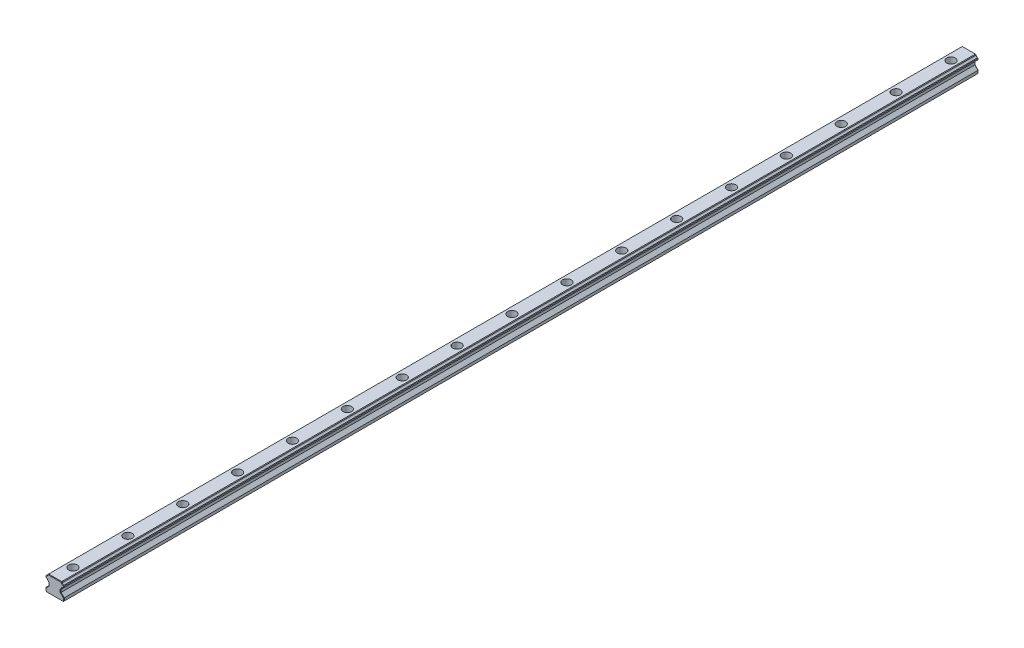
SolidWorks part; units mm, degrees
ref_plane "Front Plane" through (0, 0, 0) normal (0, 0, 1) x (1, 0, 0)
ref_plane "Top Plane" through (0, 0, 0) normal (0, 1, 0) x (1, 0, 0)
ref_plane "Right Plane" through (0, 0, 0) normal (1, 0, 0) x (0, 0, -1)
sketch "Sketch1" plane through (-20, 0, 0) normal (0, 0, 1) x (1, 0, 0)
  line L0 (10, -4.9999) -> (10, -8)
  line L1 (10, -8) -> (11, -9)
  line L2 (11, -9) -> (20, -9)
  line L3 (17, 9) -> (23, 9)
  line L5 (26.55, -1.55) -> (30, -4.9999)
  line L6 (26.55, 1.3792) -> (26.55, -1.55)
  line L7 (27.7679, 2.5951) -> (26.55, 1.3792)
  line L8 (30, 4.8292) -> (29.4727, 4.3144)
  line L9 (30, 6.16) -> (30, 4.8292)
  line L10 (29.4727, 6.6874) -> (30, 6.16)
  line L11 (27.16, 9) -> (27.7679, 8.3921)
  line L13 (29, -9) -> (20, -9)
  line L14 (30, -8) -> (29, -9)
  line L15 (30, -4.9999) -> (30, -8)
  line L16 (27.16, 9) -> (12.84, 9)
  line L17 (12.84, 9) -> (12.2321, 8.3921)
  line L18 (10.5273, 6.6874) -> (10, 6.16)
  line L19 (10, 6.16) -> (10, 4.8292)
  line L20 (10, 4.8292) -> (10.5273, 4.3144)
  line L21 (12.2321, 2.5951) -> (13.45, 1.3792)
  line L22 (13.45, 1.3792) -> (13.45, -1.55)
  line L23 (13.45, -1.55) -> (10, -4.9999)
  line L25 (20, -9) -> (20, 9) construction
  arc A0 (29.4727, 4.3144) -> (27.7679, 2.5951) centre (29.8039, 2.2812) ccw
  arc A1 (27.7679, 8.3921) -> (29.4727, 6.6874) centre (29.8015, 8.7209) ccw
  arc A2 (12.2321, 8.3921) -> (10.5273, 6.6874) centre (10.1985, 8.7209) cw
  arc A3 (10.5273, 4.3144) -> (12.2321, 2.5951) centre (10.1961, 2.2812) cw
  point P3 (20, 0.5)
  point P37 (20, 0)
  point P42 (20, 9)
  dimension "D17" = 2.06
  dimension "Rail Width" = 20
  dimension "D2" = 1
  dimension "D3" = 1
  dimension "D4" = 6
  dimension "D7" = 18
  dimension "D8" = 4.0001
  dimension "D9" = 10.55
  dimension "D10" = 13.1001
  dimension "D11" = 15.5359
  dimension "D12" = 0.6079
  dimension "D13" = 0.6079
  dimension "D15" = 0.5273
  dimension "D16" = 0.5273
  dimension "D18" = 1.2159
  dimension "D19" = 0.5148
  dimension "D20" = 6.4049
  dimension "D21" = 2.84
  dimension "D22" = 4.1708
  dimension "Rail Height" = 18
  dimension "Mounting Hole Dpeth" = 8.5
sketch "Sketch2" plane through (0, 0, 0) normal (1, 0, 0) x (0, 0, -1)
  line L0 (-480, 9) -> (-475.25, 9)
  line L1 (-475.25, 9) -> (-475.25, 0.5)
  line L2 (-475.25, 0.5) -> (-477, 0.5)
  line L3 (-477, 0.5) -> (-477, -9)
  line L4 (-477, -9) -> (-480, -9)
  line L5 (-480, -9) -> (-480, 9) construction
  line L6 (-480, -9) -> (-480, 9) construction
  line L7 (410, 0) -> (-410, 0)
  line L9 (-480, 9) -> (-480, -9)
  line L10 (500, 0) -> (-500, 0) construction
  point P6 (-360, 0)
  point P7 (-480, 0)
  point P8 (-300, 0)
  point P11 (0, 0)
  point P12 (-420, 0)
  point P13 (-180, 0)
  point P14 (-410, 0)
  point P18 (-120, 0)
  point P21 (0, 0)
  point P22 (410, 0)
  point P24 (-240, 0)
  point P25 (-60, 0)
  point P26 (0, 0)
  point P27 (60, 0)
  point P28 (120, 0)
  point P29 (180, 0)
  point P30 (240, 0)
  point P31 (300, 0)
  point P32 (360, 0)
  point P33 (420, 0)
  point P34 (480, 0)
  point P35 (410, -1)
  dimension "D1" = 9.5
  dimension "D3" = 6
  dimension "Rail Length" = 1000
  dimension "Mounting Hole Center-to-End" = 20
  dimension "Mounting Hole Center-to-Center" = 60
  dimension "D2" = 90
  dimension "D4" = 1
  dimension "Number of Mounting Holes" = 17
sketch "Sketch3" plane through (0, 0, 0) normal (0, 0, 1) x (1, 0, 0)
  line L0 (-3, 9) -> (3, 9) construction
  line L3 (-3, 9) -> (3, 9)
  line L21 (0, -9) -> (9, -9)
  line L22 (9, -9) -> (10, -8)
  line L23 (10, -8) -> (10, -4.9999)
  line L24 (10, -4.9999) -> (6.55, -1.55)
  line L25 (6.55, -1.55) -> (6.55, 1.3792)
  line L26 (6.55, 1.3792) -> (7.7679, 2.5951)
  line L27 (9.4727, 4.3144) -> (10, 4.8292)
  line L28 (10, 4.8292) -> (10, 6.16)
  line L29 (10, 6.16) -> (9.4727, 6.6874)
  line L30 (7.7679, 8.3921) -> (7.16, 9)
  line L31 (7.16, 9) -> (-7.16, 9)
  line L32 (-7.16, 9) -> (-7.7679, 8.3921)
  line L33 (-9.4727, 6.6874) -> (-10, 6.16)
  line L34 (-10, 6.16) -> (-10, 4.8292)
  line L35 (-10, 4.8292) -> (-9.4727, 4.3144)
  line L36 (-7.7679, 2.5951) -> (-6.55, 1.3792)
  line L37 (-6.55, 1.3792) -> (-6.55, -1.55)
  line L38 (-6.55, -1.55) -> (-10, -4.9999)
  line L39 (-10, -4.9999) -> (-10, -8)
  line L40 (-10, -8) -> (-9, -9)
  line L41 (-9, -9) -> (0, -9)
  line L42 (0, -9) -> (9, -9)
  line L43 (9, -9) -> (10, -8)
  line L44 (10, -8) -> (10, -4.9999)
  line L45 (10, -4.9999) -> (6.55, -1.55)
  line L46 (6.55, -1.55) -> (6.55, 1.3792)
  line L47 (6.55, 1.3792) -> (7.7679, 2.5951)
  line L48 (9.4727, 4.3144) -> (10, 4.8292)
  line L49 (10, 4.8292) -> (10, 6.16)
  line L50 (10, 6.16) -> (9.4727, 6.6874)
  line L51 (7.7679, 8.3921) -> (7.16, 9)
  line L52 (7.16, 9) -> (-7.16, 9)
  line L53 (-7.16, 9) -> (-7.7679, 8.3921)
  line L54 (-9.4727, 6.6874) -> (-10, 6.16)
  line L55 (-10, 6.16) -> (-10, 4.8292)
  line L56 (-10, 4.8292) -> (-9.4727, 4.3144)
  line L57 (-7.7679, 2.5951) -> (-6.55, 1.3792)
  line L58 (-6.55, 1.3792) -> (-6.55, -1.55)
  line L59 (-6.55, -1.55) -> (-10, -4.9999)
  line L60 (-10, -4.9999) -> (-10, -8)
  line L61 (-10, -8) -> (-9, -9)
  line L62 (-9, -9) -> (0, -9)
  arc A4 (9.4727, 4.3144) -> (7.7679, 2.5951) centre (9.8039, 2.2812) ccw
  arc A5 (7.7679, 8.3921) -> (9.4727, 6.6874) centre (9.8015, 8.7209) ccw
  arc A6 (-9.4727, 6.6874) -> (-7.7679, 8.3921) centre (-9.8015, 8.7209) ccw
  arc A7 (-7.7679, 2.5951) -> (-9.4727, 4.3144) centre (-9.8039, 2.2812) ccw
  arc A8 (9.4727, 4.3144) -> (7.7679, 2.5951) centre (9.8039, 2.2812) ccw
  arc A9 (7.7679, 8.3921) -> (9.4727, 6.6874) centre (9.8015, 8.7209) ccw
  arc A10 (-9.4727, 6.6874) -> (-7.7679, 8.3921) centre (-9.8015, 8.7209) ccw
  arc A11 (-7.7679, 2.5951) -> (-9.4727, 4.3144) centre (-9.8039, 2.2812) ccw
  dimension "D1" = 0
extrude "Boss-Extrude1" add sketch "Sketch3" along normal up to vertex (500 mm away) and the other way up to vertex (500 mm away) contours A11 L57 L58 L59 L60 L61 L62 L42 L43 L44 L45 L46 L47 A8 L48 L49 L50 A9 L51 L52 L3 L53 A10 L54 L55 L56 up to point (0, 0, 500) other way up to point (0, 0, -500)
sketch "Sketch4" plane through (0, 0, 0) normal (1, 0, 0) x (0, 0, -1)
  line L6 (-475.25, 9) -> (-480, 9)
  line L7 (-475.25, 0.5) -> (-475.25, 9)
  line L8 (-477, 0.5) -> (-475.25, 0.5)
  line L9 (-477, -9) -> (-477, 0.5)
  line L10 (-480, -9) -> (-477, -9)
  line L11 (-480, 9) -> (-480, -9)
  line L12 (-475.25, 9) -> (-480, 9)
  line L13 (-475.25, 0.5) -> (-475.25, 9)
  line L14 (-477, 0.5) -> (-475.25, 0.5)
  line L15 (-477, -9) -> (-477, 0.5)
  line L16 (-480, -9) -> (-477, -9)
  line L17 (-480, 9) -> (-480, -9)
  dimension "D1" = 0
revolve "Cut-Revolve1" cut sketch "Sketch4" angle 360 about L17
pattern_linear "LPattern2" count 17 spacing 60 along (0, 0, -1) of "Cut-Revolve1"
sketch "Sketch5" plane through (0, 0, 0) normal (0, 1, 0) x (1, 0, 0)
  line L0 (3, -480) -> (0, -480) construction
  line L1 (0, -480) -> (2.1213, -477.8787) construction
  circle A1 centre (0, -480) radius 3 construction
  circle A2 centre (0, -480) radius 3 construction
  point P3 (0, -483)
  point P4 (-3, -480)
  point P6 (3, -480)
  point P7 (2.1213, -477.8787)
  dimension "D1" = 45
sketch "Sketch6" plane through (0, 0, 0) normal (0, 0, 1) x (1, 0, 0)
  line L0 (4.75, 9) -> (-4.75, 9) construction
  line L1 (3, 0.5) -> (-3, 0.5) construction
  line L2 (4.75, 9) -> (-4.75, 9) construction
  line L3 (3, 0.5) -> (-3, 0.5) construction
  line L4 (-4.75, 9) -> (-4.75, 0.5)
  line L5 (-4.75, 0.5) -> (-3, 0.5)
  line L6 (4.75, 9) -> (4.75, 0.5)
  line L7 (4.75, 0.5) -> (3, 0.5)
  line L8 (3, 0.5) -> (3, -9)
  line L9 (-9, -9) -> (9, -9) construction
  line L10 (-3, 0.5) -> (-3, -9)
chamfer "Chamfer1" distance 0.5 angle 45 48 edges at (-7.159, 1.9872, -500) (-6.55, -0.0854, -500) (-8.275, -3.275, -500) (-10, -6.5, -500) (-9.5, -8.5, -500) (0, -9, -500) (9.5, -8.5, -500) (10, -6.5, -500) (8.275, -3.275, -500) (6.55, -0.0854, -500) (7.159, 1.9872, -500) (8.3411, 3.7316, -500) (9.7363, 4.5718, -500) (10, 5.4946, -500) (9.7363, 6.4237, -500) (8.3449, 7.2643, -500) (7.464, 8.6961, -500) (0, 9, -500) (-7.464, 8.6961, -500) (-8.3449, 7.2643, -500) (-9.7363, 6.4237, -500) (-10, 5.4946, -500) (-9.7363, 4.5718, -500) (-8.3411, 3.7316, -500) (-9.7363, 4.5718, 500) (-10, 5.4946, 500) (-9.7363, 6.4237, 500) (-8.3449, 7.2643, 500) (-7.464, 8.6961, 500) (0, 9, 500) (7.464, 8.6961, 500) (8.3449, 7.2643, 500) (9.7363, 6.4237, 500) (10, 5.4946, 500) (9.7363, 4.5718, 500) (8.3411, 3.7316, 500) (7.159, 1.9872, 500) (6.55, -0.0854, 500) (8.275, -3.275, 500) (10, -6.5, 500) (9.5, -8.5, 500) (0, -9, 500) (-9.5, -8.5, 500) (-10, -6.5, 500) (-8.275, -3.275, 500) (-6.55, -0.0854, 500) (-7.159, 1.9872, 500) (-8.3411, 3.7316, 500)
equation "\"D3@LPattern2\"=\"Mounting Hole Center-to-Center@Sketch2\""
equation "\"D1@LPattern2\"=\"Number of Mounting Holes@Sketch2\""
